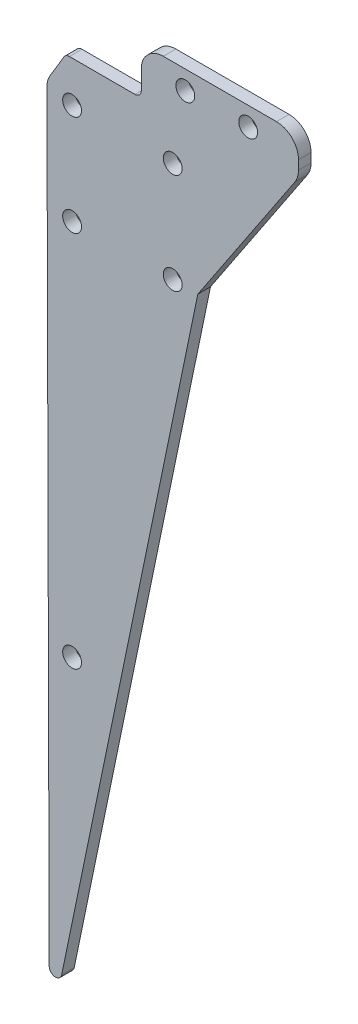
SolidWorks part; units mm, degrees
material "Thornel Mat VMA"
ref_plane "前视基准面" through (0, 0, 0) normal (0, 0, 1) x (1, 0, 0)
ref_plane "上视基准面" through (0, 0, 0) normal (0, 1, 0) x (1, 0, 0)
ref_plane "右视基准面" through (0, 0, 0) normal (1, 0, 0) x (0, 0, -1)
sketch "草图1" plane through (0, 0, 0) normal (0, 0, 1) x (1, 0, 0)
  line L0 (-12, 0) -> (25, 0) construction
  line L6 (5, -36) -> (-15, -16)
  line L7 (-15, -16) -> (-15, -12.5)
  line L9 (25, 0) -> (25, -6)
  line L10 (25, -6) -> (5, -36)
  line L11 (-12, 0) -> (-12, -7.5) construction
  line L12 (-12, -7.5) -> (-15, -12.5)
  line L13 (0, 0) -> (0, -7.5)
  line L14 (0, -7.5) -> (-12, -7.5)
  line L15 (0, 0) -> (25, 0)
  point P0 (0, 0)
  dimension "D2" = 36
  dimension "D3" = 20
  dimension "D4" = 20
  dimension "D5" = 20
  dimension "D6" = 5
  dimension "D7" = 30
  dimension "D8" = 7.5
  dimension "D9" = 25
  dimension "D10" = 12
extrude "凸台-拉伸1" add sketch "草图1" along normal blind 2
sketch "草图2" plane through (0, 0, 2) normal (0, 0, 1) x (1, 0, 0)
  line L0 (25, 0) -> (0, 0) construction
  line L1 (25, 0) -> (4, 0) construction
  line L2 (25, 0) -> (25, -6) construction
  line L3 (25, -6) -> (4, -6) construction
  line L4 (4, 0) -> (4, -6) construction
  line L5 (14.5, 0) -> (14.5, -6) construction
  line L6 (25, 0) -> (0, 0) construction
  circle A0 centre (17, -3) radius 1.5
  circle A1 centre (7, -3) radius 1.5
  point P9 (12.5, 0)
  dimension "D4" = 3
  dimension "D5" = 3
  dimension "D1" = 21
  dimension "D2" = 8
  dimension "D3" = 10
  dimension "D6" = 3
  dimension "D7" = 6
  dimension "D8" = 2
extrude "切除-拉伸1" cut sketch "草图2" against normal blind 5
sketch "草图3" plane through (0, 0, 2) normal (0, 0, 1) x (1, 0, 0)
  circle A0 centre (5, -30) radius 1.5
  circle A1 centre (5, -14) radius 1.5
  circle A2 centre (-11, -14) radius 1.5
  dimension "D1" = 3
  dimension "D2" = 3
  dimension "D6" = 3
  dimension "D3" = 6
  dimension "D4" = 16
  dimension "D5" = 0
  dimension "D7" = 16
extrude "切除-拉伸2" cut sketch "草图3" against normal blind 10
fillet "圆角1" radius 3.5 6 edges at (-15, -16, 1) (5, -36, 1) (25, -6, 1) (-15, -12.5, 1) (0, 0, 1) (25, 0, 1)
fillet "圆角2" radius 1 2 edges at (0, -7.5, 1) (-12, -7.5, 1)
sketch "草图4" plane through (0, 0, 2) normal (0, 0, 1) x (1, 0, 0)
  line L0 (9, -30) -> (-12.6603, -134.5918)
  line L1 (7.3682, -32.4477) -> (24.4122, -6.8817) construction
  line L2 (-14.6395, -134.392) -> (-15, -14.0098)
  line L3 (-15, -14.0098) -> (9, -30)
  line L5 (-15, -13.4694) -> (-15, -14.5503) construction
  circle A1 centre (-11, -30) radius 1.5
  circle A2 centre (-11, -90) radius 1.5
  circle A3 centre (-11, -14) radius 1.5 construction
  circle A4 centre (5, -30) radius 1.5 construction
  arc A5 (-12.6603, -134.5918) -> (-14.6395, -134.392) centre (-13.6395, -134.389) cw
  circle A6 centre (5, -30) radius 1.5 construction
  circle A7 centre (5, -30) radius 1.5
  point P6 (-15, -14.0098)
  point P16 (-14.7336, -15.8896)
  point P17 (0, 0)
  point P18 (-147.4176, -8.6541)
  point P21 (-14.6107, -144.0098)
  dimension "D2" = 3
  dimension "D3" = 16
  dimension "D6" = 1
  dimension "D1" = 130
  dimension "D4" = 16
  dimension "D5" = 60
extrude "凸台-拉伸2" add sketch "草图4" against normal up to surface (2 mm away) up to face at (3.5, -30, 0)
